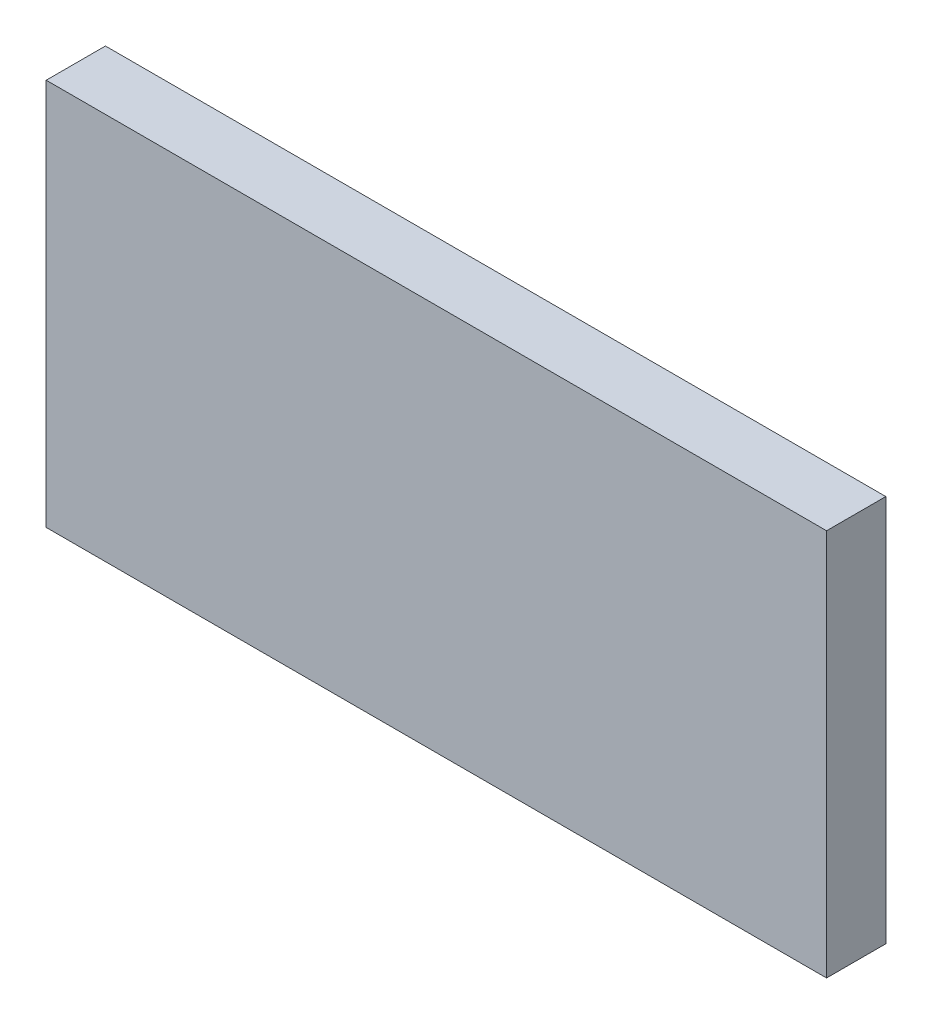
SolidWorks part; units mm, degrees
ref_plane "前基準面" through (0, 0, 0) normal (0, 0, 1) x (1, 0, 0)
ref_plane "上基準面" through (0, 0, 0) normal (0, 1, 0) x (1, 0, 0)
ref_plane "右基準面" through (0, 0, 0) normal (1, 0, 0) x (0, 0, -1)
sketch "草圖1" plane through (0, 0, 0) normal (0, 0, 1) x (1, 0, 0)
  line L1 (-5.4448, 2.8878) -> (131.5552, 2.8878)
  line L2 (-5.4448, 2.8878) -> (-5.4448, -65.1122)
  line L3 (-5.4448, -65.1122) -> (131.5552, -65.1122)
  line L4 (131.5552, 2.8878) -> (131.5552, -65.1122)
  dimension "D1" = 68
  dimension "D2" = 137
extrude "填料-伸長1" add sketch "草圖1" along normal blind 10.4
